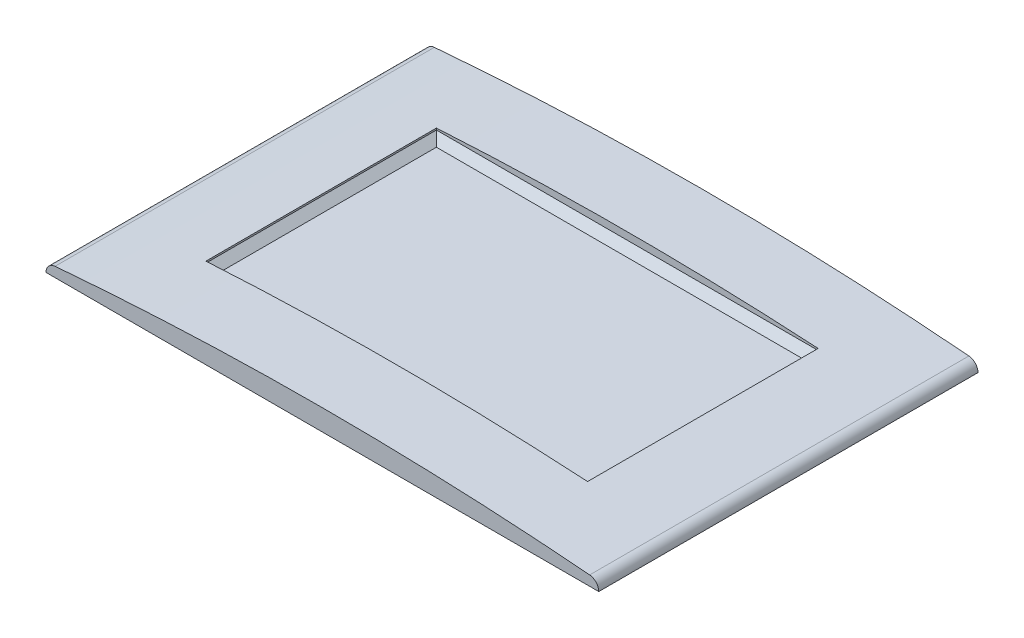
SolidWorks part; units mm, degrees
ref_plane "Front Plane" through (0, 0, 0) normal (0, 0, 1) x (1, 0, 0)
ref_plane "Top Plane" through (0, 0, 0) normal (0, 1, 0) x (1, 0, 0)
ref_plane "Right Plane" through (0, 0, 0) normal (1, 0, 0) x (0, 0, -1)
sketch "Sketch1" plane through (0, 0, 0) normal (0, 1, 0) x (1, 0, 0)
  line L1 (-111.5, -76.5) -> (111.5, -76.5)
  line L2 (-111.5, -76.5) -> (-111.5, 76.5)
  line L3 (-111.5, 76.5) -> (111.5, 76.5)
  line L4 (111.5, -76.5) -> (111.5, 76.5)
  line L5 (-111.5, -76.5) -> (111.5, 76.5) construction
  line L6 (-111.5, 76.5) -> (111.5, -76.5) construction
  point P0 (0, 0)
  dimension "D1" = 223
  dimension "D2" = 153
extrude "Boss-Extrude2" add sketch "Sketch1" along normal blind 8.5
sketch "Sketch3" plane through (0, 8.5, 0) normal (0, 1, 0) x (1, 0, 0)
  line L1 (-77, 46.5) -> (77, 46.5)
  line L2 (-77, 46.5) -> (-77, -46.5)
  line L3 (-77, -46.5) -> (77, -46.5)
  line L4 (77, 46.5) -> (77, -46.5)
  line L5 (-77, 46.5) -> (77, -46.5) construction
  line L6 (-77, -46.5) -> (77, 46.5) construction
  point P0 (0, 0)
  dimension "D1" = 154
  dimension "D2" = 93
extrude "Cut-Extrude1" cut sketch "Sketch3" against normal blind 6
sketch "Sketch4" plane through (0, 0, 0) normal (0, 0, 1) x (1, 0, 0)
  line L0 (0, -4.675) -> (0, 4.675) construction
  line L1 (-111.5, 0) -> (111.5, 0) construction
  line L2 (-111.5, 8.5) -> (-111.5, 0) construction
  line L3 (111.5, 8.5) -> (-111.5, 8.5) construction
  line L4 (111.5, 8.5) -> (111.5, 0) construction
  line L5 (-111.5, 8.5) -> (-111.5, 0)
  line L6 (111.5, 8.5) -> (-111.5, 8.5)
  line L7 (111.5, 8.5) -> (111.5, 0)
  arc A0 (107.8343, 3.986) -> (111.5, 0) centre (107.5, 0) cw
  arc A1 (-107.8343, 3.986) -> (-111.5, 0) centre (-107.5, 0) ccw
  arc A3 (-107.8343, 3.986) -> (107.8343, 3.986) centre (0, -1281.7778) cw
  point P0 (111.5, 0)
  point P1 (-111.5, 0)
  point P11 (0, 8.5)
  dimension "D2" = 4
  dimension "D1" = 8.5
extrude "Cut-Extrude3" cut sketch "Sketch4" against normal up to surface and the other way up to surface contours A1 A3 L6 L5 | L6 A3 A0 L7 up to face at (0, 4.25, -76.5) other way up to face at (0, 4.25, 76.5)
chamfer "Chamfer2" distance 3 angle 45 4 edges at (0, 2.5, 46.5) (77, 2.5, 0) (-77, 2.5, 0) (0, 2.5, -46.5)
